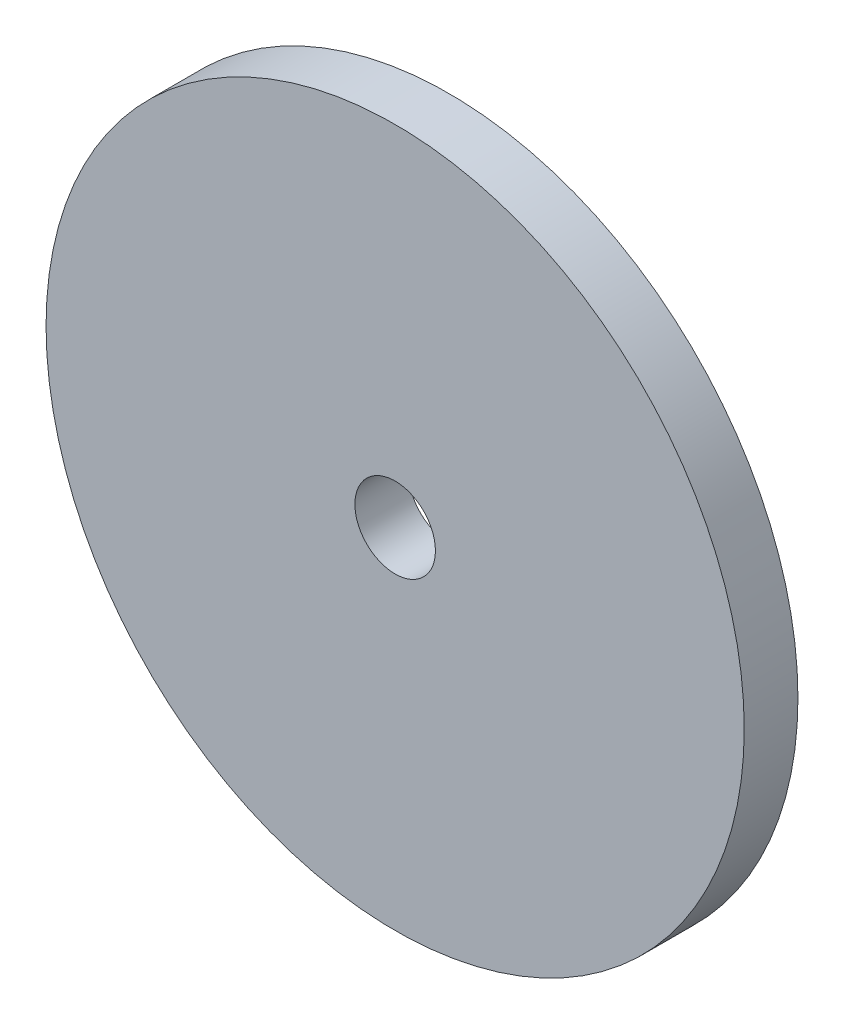
SolidWorks part; units mm, degrees
ref_plane "Front Plane" through (0, 0, 0) normal (0, 0, 1) x (1, 0, 0)
ref_plane "Top Plane" through (0, 0, 0) normal (0, 1, 0) x (1, 0, 0)
ref_plane "Right Plane" through (0, 0, 0) normal (1, 0, 0) x (0, 0, -1)
sketch "Sketch1" plane through (0, 0, 0) normal (0, 0, 1) x (1, 0, 0)
  circle A0 centre (0, 0) radius 13
  dimension "D1" = 26
extrude "Boss-Extrude1" add sketch "Sketch1" along normal blind 2 contours A0
sketch "Sketch2" plane through (0, 0, 2) normal (0, 0, 1) x (1, 0, 0)
  circle A0 centre (0, 0) radius 1.5
  dimension "3" = 3
extrude "Cut-Extrude1" cut sketch "Sketch2" against normal blind 10 contours A0
